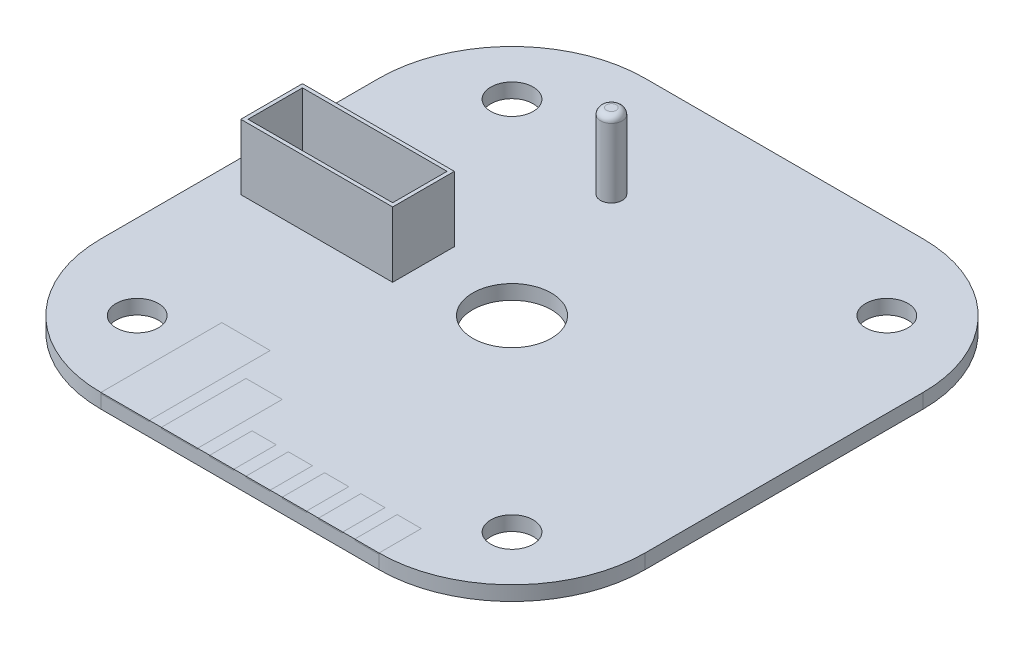
SolidWorks part; units mm, degrees
ref_plane "Front Plane" through (0, 0, 0) normal (0, 0, 1) x (1, 0, 0)
ref_plane "Top Plane" through (0, 0, 0) normal (0, 1, 0) x (1, 0, 0)
ref_plane "Right Plane" through (0, 0, 0) normal (1, 0, 0) x (0, 0, -1)
sketch "Sketch1" plane through (0, 0, 0) normal (0, 1, 0) x (1, 0, 0)
  line L1 (-22.5, -22.5) -> (22.5, -22.5)
  line L2 (-22.5, -22.5) -> (-22.5, 22.5)
  line L3 (-22.5, 22.5) -> (22.5, 22.5)
  line L4 (22.5, -22.5) -> (22.5, 22.5)
  line L5 (-22.5, -22.5) -> (22.5, 22.5) construction
  line L6 (-22.5, 22.5) -> (22.5, -22.5) construction
  point P0 (0, 0)
  dimension "D1" = 45
extrude "Boss-Extrude1" add sketch "Sketch1" along normal mid plane 1.2
sketch "Sketch3" plane through (0, 0, 0) normal (0, 1, 0) x (1, 0, 0)
  circle A0 centre (0, 0) radius 3.25
  dimension "D1" = 6.5
extrude "Cut-Extrude1" cut sketch "Sketch3" against normal through all both and the other way through all
fillet "Fillet1" radius 11 4 edges at (22.5, 0, 22.5) (-22.5, 0, 22.5) (-22.5, 0, -22.5) (22.5, 0, -22.5)
sketch "Sketch5" plane through (0, 0, 0) normal (0, 1, 0) x (1, 0, 0)
  line L0 (-15.5, -15.5) -> (15.5, 15.5) construction
  line L1 (-15.5, 15.5) -> (15.5, -15.5) construction
  line L2 (0, 0) -> (0, 21.9203) construction
  circle A0 centre (0, 0) radius 21.9203 construction
  circle A1 centre (-15.5, 15.5) radius 1.75
  circle A2 centre (15.5, 15.5) radius 1.75
  circle A3 centre (15.5, -15.5) radius 1.75
  circle A4 centre (-15.5, -15.5) radius 1.75
  point P6 (0, 0)
  point P9 (0, 0)
  dimension "D2" = 3.5
  dimension "D3" = 31
  dimension "D1" = 45
extrude "Cut-Extrude2" cut sketch "Sketch5" against normal through all both and the other way through all
sketch "Sketch6" plane through (0, 0.6, 0) normal (0, 1, 0) x (1, 0, 0)
  line L0 (-13.6, 0) -> (0, 0) construction
  line L1 (-19.88, -2.55) -> (-7.32, -2.55)
  line L2 (-19.88, -2.55) -> (-19.88, 2.55)
  line L3 (-19.88, 2.55) -> (-7.32, 2.55)
  line L4 (-7.32, -2.55) -> (-7.32, 2.55)
  line L5 (-19.88, -2.55) -> (-7.32, 2.55) construction
  line L6 (-19.88, 2.55) -> (-7.32, -2.55) construction
  point P0 (-13.6, 0)
  dimension "D3" = 13.6
  dimension "D1" = 12.56
  dimension "D2" = 5.1
extrude "Extrude-Thin1" add sketch "Sketch6" along normal blind 5.4 thin thin type one direction reverse wall 0.3
sketch "Sketch7" plane through (0, 0.6, 0) normal (0, 1, 0) x (1, 0, 0)
  line L0 (-7.62, -2.25) -> (-7.62, 2.25) construction
  line L1 (-19.58, -2.25) -> (-7.62, -2.25) construction
  line L2 (-19.58, 2.25) -> (-19.58, -2.25) construction
  line L3 (-7.62, 2.25) -> (-19.58, 2.25) construction
  line L4 (-7.62, -2.25) -> (-7.62, 2.25)
  line L5 (-19.58, -2.25) -> (-7.62, -2.25)
  line L6 (-19.58, 2.25) -> (-19.58, -2.25)
  line L7 (-7.62, 2.25) -> (-19.58, 2.25)
extrude "Boss-Extrude2" add sketch "Sketch7" along normal blind 0.3
sketch "Sketch8" plane through (0, 0.6, 0) normal (0, 1, 0) x (1, 0, 0)
  line L0 (-11.5, -22.5) -> (11.5, -22.5) construction
  line L1 (-2.5, -22.5) -> (-0.5, -22.5)
  line L2 (-2.5, -22.5) -> (-2.5, -19)
  line L3 (-2.5, -19) -> (-0.5, -19)
  line L4 (-0.5, -22.5) -> (-0.5, -19)
  line L5 (-0.5, -19) -> (0.5, -19) construction
  line L6 (0.5, -22.5) -> (2.5, -22.5)
  line L7 (0.5, -22.5) -> (0.5, -19)
  line L8 (0.5, -19) -> (2.5, -19)
  line L9 (2.5, -22.5) -> (2.5, -19)
  line L10 (3.5, -22.5) -> (5.5, -22.5)
  line L11 (3.5, -22.5) -> (3.5, -19)
  line L12 (3.5, -19) -> (5.5, -19)
  line L13 (5.5, -22.5) -> (5.5, -19)
  line L14 (6.5, -22.5) -> (8.5, -22.5)
  line L15 (6.5, -22.5) -> (6.5, -19)
  line L16 (6.5, -19) -> (8.5, -19)
  line L17 (8.5, -22.5) -> (8.5, -19)
  line L18 (9.5, -22.5) -> (11.5, -22.5)
  line L19 (9.5, -22.5) -> (9.5, -19)
  line L20 (9.5, -19) -> (11.5, -19)
  line L21 (11.5, -22.5) -> (11.5, -19)
  line L22 (2.5, -19) -> (3.5, -19) construction
  line L23 (5.5, -19) -> (6.5, -19) construction
  line L24 (8.5, -19) -> (9.5, -19) construction
  line L26 (-11.5, -22.5) -> (-7.5, -22.5)
  line L27 (-11.5, -22.5) -> (-11.5, -12.5)
  line L28 (-11.5, -12.5) -> (-7.5, -12.5)
  line L29 (-7.5, -22.5) -> (-7.5, -12.5)
  line L30 (-6.5, -22.5) -> (-3.5, -22.5)
  line L31 (-6.5, -22.5) -> (-6.5, -15.5)
  line L32 (-6.5, -15.5) -> (-3.5, -15.5)
  line L33 (-3.5, -22.5) -> (-3.5, -15.5)
  dimension "D1" = 2
  dimension "D2" = 1
  dimension "D3" = 3.5
  dimension "D4" = 10
  dimension "D5" = 4
  dimension "D6" = 1
  dimension "D7" = 3
  dimension "D8" = 7
  dimension "D9" = 1
extrude "Cut-Extrude3" cut sketch "Sketch8" against normal blind 0.1
sketch "Sketch9" plane through (0, 0.5, 0) normal (0, 1, 0) x (1, 0, 0)
  line L0 (9.5, -19) -> (9.5, -22.5) construction
  line L1 (9.5, -22.5) -> (11.5, -22.5) construction
  line L2 (11.5, -22.5) -> (11.5, -19) construction
  line L3 (11.5, -19) -> (9.5, -19) construction
  line L4 (6.5, -19) -> (6.5, -22.5) construction
  line L5 (6.5, -22.5) -> (8.5, -22.5) construction
  line L6 (8.5, -22.5) -> (8.5, -19) construction
  line L7 (8.5, -19) -> (6.5, -19) construction
  line L8 (3.5, -19) -> (3.5, -22.5) construction
  line L9 (3.5, -22.5) -> (5.5, -22.5) construction
  line L10 (5.5, -22.5) -> (5.5, -19) construction
  line L11 (5.5, -19) -> (3.5, -19) construction
  line L12 (0.5, -19) -> (0.5, -22.5) construction
  line L13 (0.5, -22.5) -> (2.5, -22.5) construction
  line L14 (2.5, -22.5) -> (2.5, -19) construction
  line L15 (2.5, -19) -> (0.5, -19) construction
  line L16 (-2.5, -19) -> (-2.5, -22.5) construction
  line L17 (-2.5, -22.5) -> (-0.5, -22.5) construction
  line L18 (-0.5, -22.5) -> (-0.5, -19) construction
  line L19 (-0.5, -19) -> (-2.5, -19) construction
  line L20 (-6.5, -15.5) -> (-6.5, -22.5) construction
  line L21 (-6.5, -22.5) -> (-3.5, -22.5) construction
  line L22 (-3.5, -22.5) -> (-3.5, -15.5) construction
  line L23 (-3.5, -15.5) -> (-6.5, -15.5) construction
  line L24 (-11.5, -12.5) -> (-11.5, -22.5) construction
  line L25 (-11.5, -22.5) -> (-7.5, -22.5) construction
  line L26 (-7.5, -22.5) -> (-7.5, -12.5) construction
  line L27 (-7.5, -12.5) -> (-11.5, -12.5) construction
  line L28 (9.5, -19) -> (9.5, -22.5)
  line L29 (9.5, -22.5) -> (11.5, -22.5)
  line L30 (11.5, -22.5) -> (11.5, -19)
  line L31 (11.5, -19) -> (9.5, -19)
  line L32 (6.5, -19) -> (6.5, -22.5)
  line L33 (6.5, -22.5) -> (8.5, -22.5)
  line L34 (8.5, -22.5) -> (8.5, -19)
  line L35 (8.5, -19) -> (6.5, -19)
  line L36 (3.5, -19) -> (3.5, -22.5)
  line L37 (3.5, -22.5) -> (5.5, -22.5)
  line L38 (5.5, -22.5) -> (5.5, -19)
  line L39 (5.5, -19) -> (3.5, -19)
  line L40 (0.5, -19) -> (0.5, -22.5)
  line L41 (0.5, -22.5) -> (2.5, -22.5)
  line L42 (2.5, -22.5) -> (2.5, -19)
  line L43 (2.5, -19) -> (0.5, -19)
  line L44 (-2.5, -19) -> (-2.5, -22.5)
  line L45 (-2.5, -22.5) -> (-0.5, -22.5)
  line L46 (-0.5, -22.5) -> (-0.5, -19)
  line L47 (-0.5, -19) -> (-2.5, -19)
  line L48 (-6.5, -15.5) -> (-6.5, -22.5)
  line L49 (-6.5, -22.5) -> (-3.5, -22.5)
  line L50 (-3.5, -22.5) -> (-3.5, -15.5)
  line L51 (-3.5, -15.5) -> (-6.5, -15.5)
  line L52 (-11.5, -12.5) -> (-11.5, -22.5)
  line L53 (-11.5, -22.5) -> (-7.5, -22.5)
  line L54 (-7.5, -22.5) -> (-7.5, -12.5)
  line L55 (-7.5, -12.5) -> (-11.5, -12.5)
extrude "Boss-Extrude3" add sketch "Sketch9" along normal up to surface (0.1 mm away) separate body up to face at (-15.5, 0.6, 17.25)
sketch "Sketch10" plane through (0, 0.6, 0) normal (0, 1, 0) x (1, 0, 0)
  line L0 (-2.5, -9.5) -> (-2.5, -13.6) construction
  line L1 (3.5, -9.5) -> (3.5, -13.6) construction
  line L2 (-2.5, -11.55) -> (3.5, -11.55) construction
  circle A0 centre (3.5, -9.5) radius 0.9 construction
  circle A1 centre (3.5, -13.6) radius 1.65 construction
  circle A2 centre (-2.5, -13.6) radius 1.65 construction
  circle A3 centre (-2.5, -9.5) radius 0.9 construction
  circle A4 centre (-4.59, 12.81) radius 0.9
  circle A5 centre (-15.5, 15.5) radius 1.75 construction
  circle A6 centre (0, 0) radius 3.25 construction
  dimension "D1" = 1.8
  dimension "D2" = 3.3
  dimension "D3" = 19
  dimension "D4" = 25
  dimension "D5" = 29.1
  dimension "D6" = 4.59
  dimension "D7" = 13
  dimension "D8" = 12.81
extrude "Boss-Extrude4" add sketch "Sketch10" along normal blind 6.2
fillet "Fillet2" radius 0.5 1 edges at (-4.59, 6.8, -11.91)
